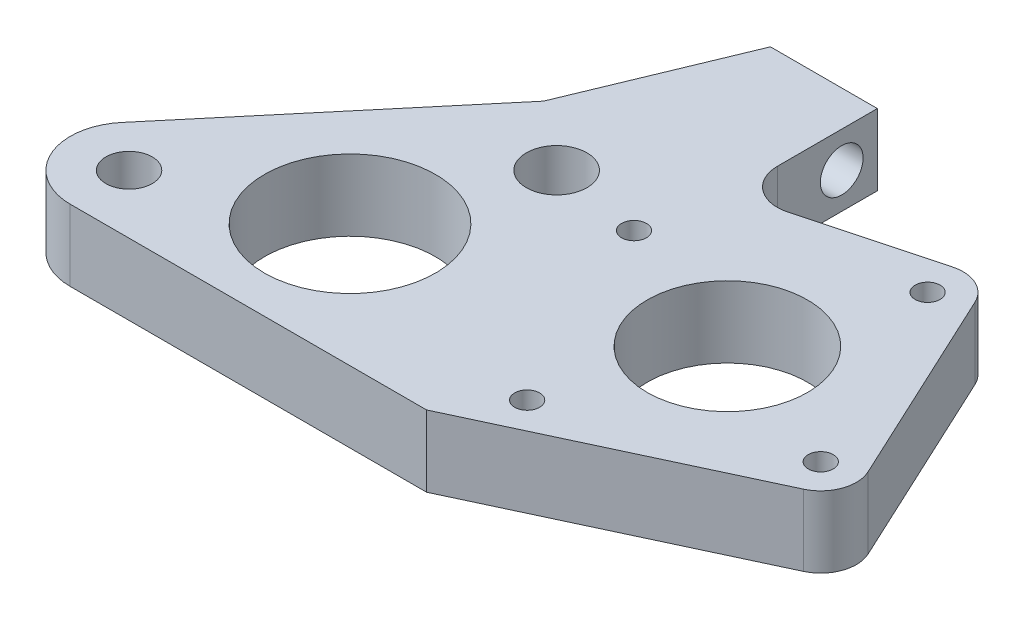
SolidWorks part; units mm, degrees
material "ABS PC"
ref_plane "Спереди" through (0, 0, 0) normal (0, 0, 1) x (1, 0, 0)
ref_plane "Сверху" through (0, 0, 0) normal (0, 1, 0) x (1, 0, 0)
ref_plane "Справа" through (0, 0, 0) normal (1, 0, 0) x (0, 0, -1)
sketch "Sketch1" plane through (0, 0, 0) normal (0, 1, 0) x (1, 0, 0)
  line L0 (42.76, 28.0955) -> (55.8612, 0) construction
  line L1 (55.8612, 0) -> (83.9567, 13.1012) construction
  line L2 (83.9567, 13.1012) -> (70.8555, 41.1967) construction
  line L3 (70.8555, 41.1967) -> (42.76, 28.0955) construction
  line L4 (49.3106, 14.0478) -> (63.3584, 20.5984) construction
  line L5 (63.3584, 20.5984) -> (56.8078, 34.6461) construction
  line L6 (0, -8.25) -> (50, -8.25)
  line L7 (50, -8.25) -> (86.0698, 8.5696)
  line L8 (88.4883, 15.2143) -> (75.3871, 43.3098)
  line L9 (45, 39.4451) -> (69.5615, 46.0263)
  line L10 (20.6772, 37.4769) -> (-6.3199, 5.303)
  line L11 (45, 39.4451) -> (45, 60)
  line L12 (45, 60) -> (30, 60)
  line L13 (30, 60) -> (20.6772, 37.4769)
  circle A0 centre (0, 0) radius 3.25
  circle A1 centre (30, 30) radius 4.25
  circle A2 centre (63.3584, 20.5984) radius 11.25
  circle A3 centre (42.76, 28.0955) radius 1.75
  circle A4 centre (70.8555, 41.1967) radius 1.75
  circle A5 centre (83.9567, 13.1012) radius 1.75
  circle A6 centre (55.8612, 0) radius 1.75
  arc A8 (-6.3199, 5.303) -> (0, -8.25) centre (0, 0) ccw
  circle A9 centre (22, 9) radius 12
  arc A10 (69.5615, 46.0263) -> (75.3871, 43.3098) centre (70.8555, 41.1967) cw
  arc A11 (86.0698, 8.5696) -> (88.4883, 15.2143) centre (83.9567, 13.1012) ccw
  dimension "D1" = 3.5
  dimension "D4" = 8.5
  dimension "D5" = 6.5
  dimension "D7" = 22.5
  dimension "D12" = 5
  dimension "D13" = 42
  dimension "D15" = 24
  dimension "D16" = 22
  dimension "D17" = 9
  dimension "D14" = 50
  dimension "D2" = 30
  dimension "D3" = 30
  dimension "D6" = 31
  dimension "D8" = 5
  dimension "D9" = 15
  dimension "D10" = 65
  dimension "D11" = 50
  dimension "D18" = 30
  dimension "D19" = 100
extrude "Boss-Extrude1" add sketch "Sketch1" along normal blind 10
fillet "Fillet1" radius 5 1 edges at (45, 5, -39.4451)
sketch "Sketch2" plane through (45, 0, 0) normal (1, 0, 0) x (0, 0, -1)
  line L0 (45.9612, 10) -> (60, 10) construction
  line L1 (60, 10) -> (60, 0) construction
  circle A0 centre (55, 5) radius 3
  dimension "D1" = 6
  dimension "D2" = 5
  dimension "D3" = 5
extrude "Cut-Extrude1" cut sketch "Sketch2" against normal blind 10
